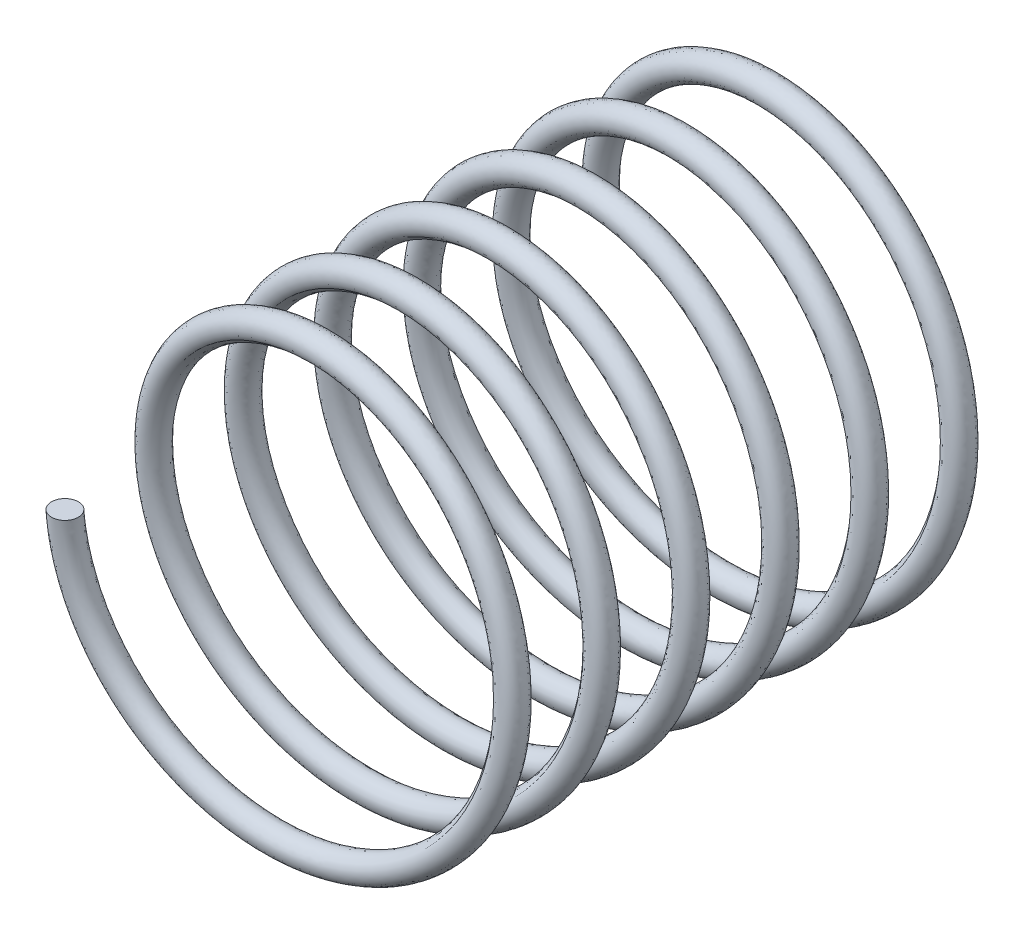
SolidWorks part; units mm, degrees
material "Stainless Steel (ferritic)"
ref_plane "Front Plane" through (0, 0, 0) normal (0, 0, 1) x (1, 0, 0)
ref_plane "Top Plane" through (0, 0, 0) normal (0, 1, 0) x (1, 0, 0)
ref_plane "Right Plane" through (0, 0, 0) normal (1, 0, 0) x (0, 0, -1)
sketch "Sketch1" plane through (0, 0, 0) normal (0, 0, 1) x (1, 0, 0)
  circle A0 centre (0, 0) radius 4.5
  dimension "D1" = 9
curve "Helix/Spiral1" pitch 2 height 12 turns 6
ref_plane "Plane1" through (0, 0, 0) normal (0, 1, 0) x (1, 0, 0)
sketch "Sketch2" plane through (0, 0, 0) normal (0, 1, 0) x (1, 0, 0)
  circle A0 centre (-4.5, -12) radius 0.3
  spline S0 degree 3 poles (-4.5, 0) (-4.5, -0.0414) (-4.2657, -0.1251) (-3.2648, -0.25) (-1.7669, -0.375) (0, -0.5) (1.7669, -0.625) (3.2648, -0.75) (4.2657, -0.875) (4.6172, -1) (4.2657, -1.125) (3.2648, -1.25) (1.7669, -1.375) (0, -1.5) (-1.7669, -1.625) (-3.2648, -1.75) (-4.2657, -1.875) (-4.6172, -2) (-4.2657, -2.125) (-3.2648, -2.25) (-1.7669, -2.375) (0, -2.5) (1.7669, -2.625) (3.2648, -2.75) (4.2657, -2.875) (4.6172, -3) (4.2657, -3.125) (3.2648, -3.25) (1.7669, -3.375) (0, -3.5) (-1.7669, -3.625) (-3.2648, -3.75) (-4.2657, -3.875) (-4.6172, -4) (-4.2657, -4.125) (-3.2648, -4.25) (-1.7669, -4.375) (0, -4.5) (1.7669, -4.625) (3.2648, -4.75) (4.2657, -4.875) (4.6172, -5) (4.2657, -5.125) (3.2648, -5.25) (1.7669, -5.375) (0, -5.5) (-1.7669, -5.625) (-3.2648, -5.75) (-4.2657, -5.875) (-4.6172, -6) (-4.2657, -6.125) (-3.2648, -6.25) (-1.7669, -6.375) (0, -6.5) (1.7669, -6.625) (3.2648, -6.75) (4.2657, -6.875) (4.6172, -7) (4.2657, -7.125) (3.2648, -7.25) (1.7669, -7.375) (0, -7.5) (-1.7669, -7.625) (-3.2648, -7.75) (-4.2657, -7.875) (-4.6172, -8) (-4.2657, -8.125) (-3.2648, -8.25) (-1.7669, -8.375) (0, -8.5) (1.7669, -8.625) (3.2648, -8.75) (4.2657, -8.875) (4.6172, -9) (4.2657, -9.125) (3.2648, -9.25) (1.7669, -9.375) (0, -9.5) (-1.7669, -9.625) (-3.2648, -9.75) (-4.2657, -9.875) (-4.6172, -10) (-4.2657, -10.125) (-3.2648, -10.25) (-1.7669, -10.375) (0, -10.5) (1.7669, -10.625) (3.2648, -10.75) (4.2657, -10.875) (4.6172, -11) (4.2657, -11.125) (3.2648, -11.25) (1.7669, -11.375) (0, -11.5) (-1.7669, -11.625) (-3.2648, -11.75) (-4.2657, -11.8749) (-4.5, -11.9586) (-4.5, -12) knots 0 0 0 0 0.010417 0.020833 0.03125 0.041667 0.052083 0.0625 0.072917 0.083333 0.09375 0.104167 0.114583 0.125 0.135417 0.145833 0.15625 0.166667 0.177083 0.1875 0.197917 0.208333 0.21875 0.229167 0.239583 0.25 0.260417 0.270833 0.28125 0.291667 0.302083 0.3125 0.322917 0.333333 0.34375 0.354167 0.364583 0.375 0.385417 0.395833 0.40625 0.416667 0.427083 0.4375 0.447917 0.458333 0.46875 0.479167 0.489583 0.5 0.510417 0.520833 0.53125 0.541667 0.552083 0.5625 0.572917 0.583333 0.59375 0.604167 0.614583 0.625 0.635417 0.645833 0.65625 0.666667 0.677083 0.6875 0.697917 0.708333 0.71875 0.729167 0.739583 0.75 0.760417 0.770833 0.78125 0.791667 0.802083 0.8125 0.822917 0.833333 0.84375 0.854167 0.864583 0.875 0.885417 0.895833 0.90625 0.916667 0.927083 0.9375 0.947917 0.958333 0.96875 0.979167 0.989583 1 1 1 1 construction
  dimension "D1" = 0.6
sweep "Sweep1" add profiles "Sketch2" path "Helix/Spiral1"
